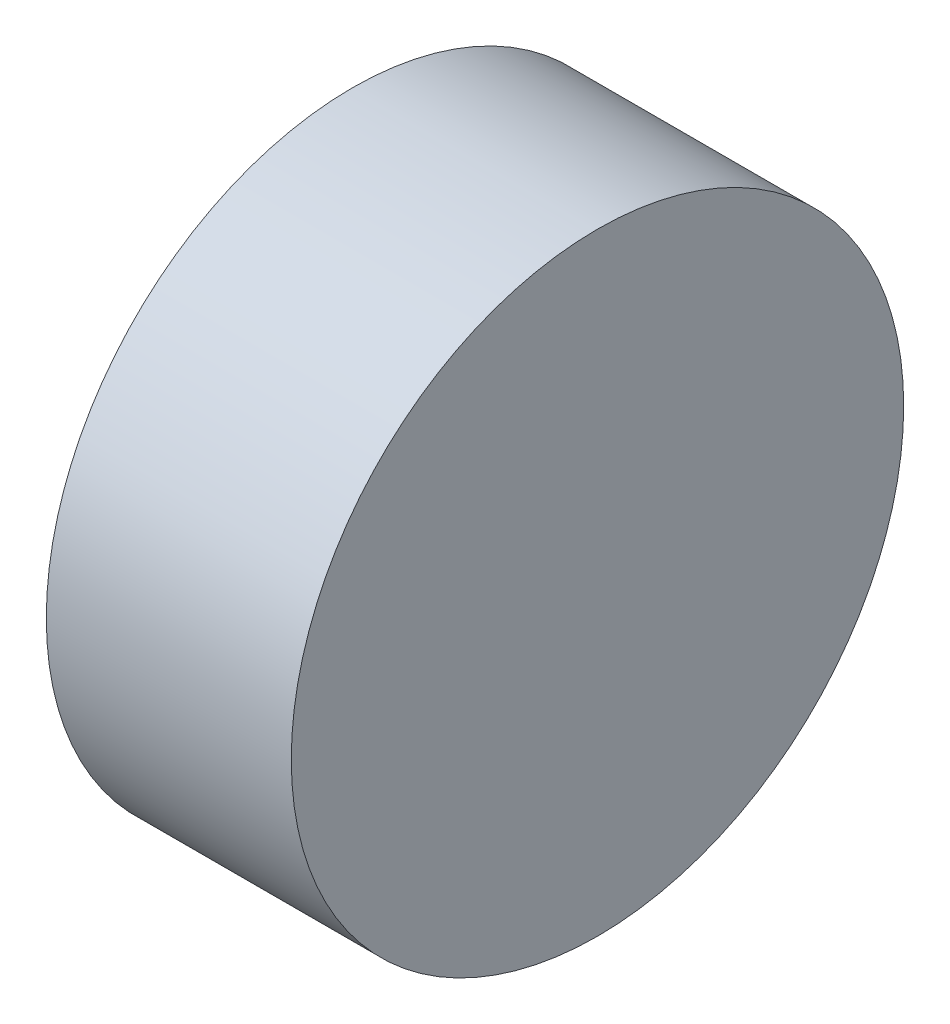
SolidWorks part; units mm, degrees
ref_plane "前视基准面" through (0, 0, 0) normal (0, 0, 1) x (1, 0, 0)
ref_plane "上视基准面" through (0, 0, 0) normal (0, 1, 0) x (1, 0, 0)
ref_plane "右视基准面" through (0, 0, 0) normal (1, 0, 0) x (0, 0, -1)
sketch "草图1" plane through (0, 0, 0) normal (1, 0, 0) x (0, 0, -1)
  circle A0 centre (0, 0) radius 10
  dimension "D1" = 20
extrude "凸台-拉伸1" add sketch "草图1" along normal mid plane 8
sketch "草图2" plane through (-4, 0, 0) normal (-1, 0, 0) x (0, 0, 1)
  circle A0 centre (0, 0) radius 6.5
  circle A1 centre (0, 0) radius 2
  circle A2 centre (0, 0) radius 1
  dimension "D1" = 13
  dimension "D2" = 2
  dimension "D3" = 4
extrude "切除-拉伸1" cut sketch "草图2" against normal blind 6 contours A0 A1 | A2
